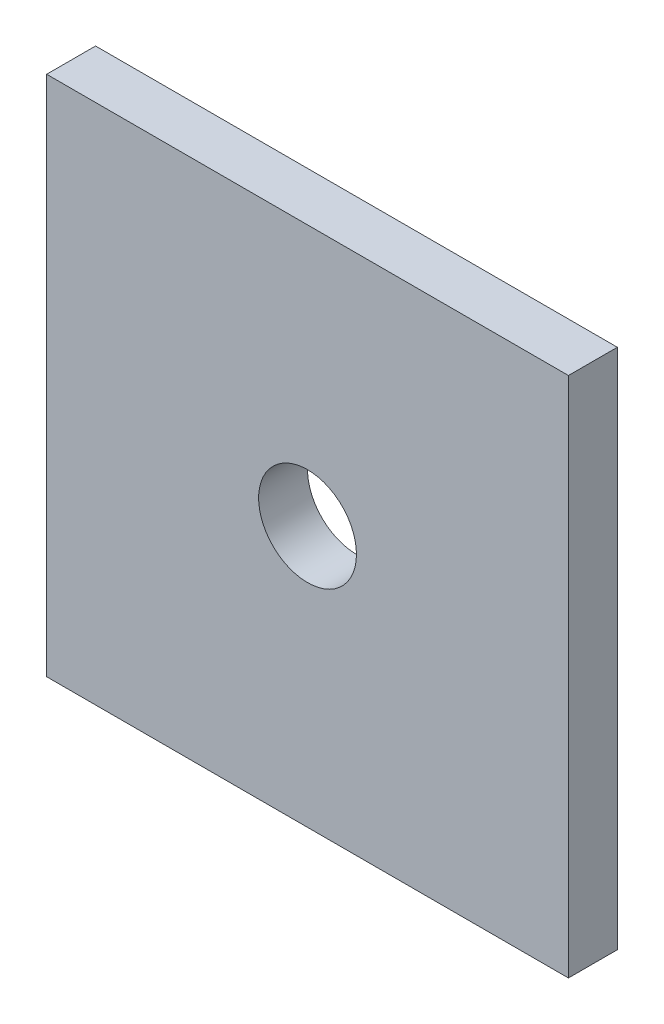
SolidWorks part; units mm, degrees
ref_plane "Plan de face" through (0, 0, 0) normal (0, 0, 1) x (1, 0, 0)
ref_plane "Plan de dessus" through (0, 0, 0) normal (0, 1, 0) x (1, 0, 0)
ref_plane "Plan de droite" through (0, 0, 0) normal (1, 0, 0) x (0, 0, -1)
sketch "Esquisse1" plane through (0, 0, 0) normal (0, 0, 1) x (1, 0, 0)
  line L1 (-13.4748, 19.0476) -> (18.5252, 19.0476)
  line L2 (-13.4748, 19.0476) -> (-13.4748, -12.9524)
  line L3 (-13.4748, -12.9524) -> (18.5252, -12.9524)
  line L4 (18.5252, 19.0476) -> (18.5252, -12.9524)
  dimension "D1" = 32
  dimension "D2" = 32
extrude "Boss.-Extru.1" add sketch "Esquisse1" along normal blind 3
sketch "Esquisse2" plane through (0, 0, 3) normal (0, 0, 1) x (1, 0, 0)
  line L0 (18.5252, -12.9524) -> (18.5252, 19.0476) construction
  line L1 (-13.4748, -12.9524) -> (18.5252, -12.9524) construction
  circle A0 centre (2.5252, 3.0476) radius 3
  dimension "D1" = 6
  dimension "D2" = 16
  dimension "D3" = 16
extrude "Enlèv. mat.-Extru.1" cut sketch "Esquisse2" against normal through all
